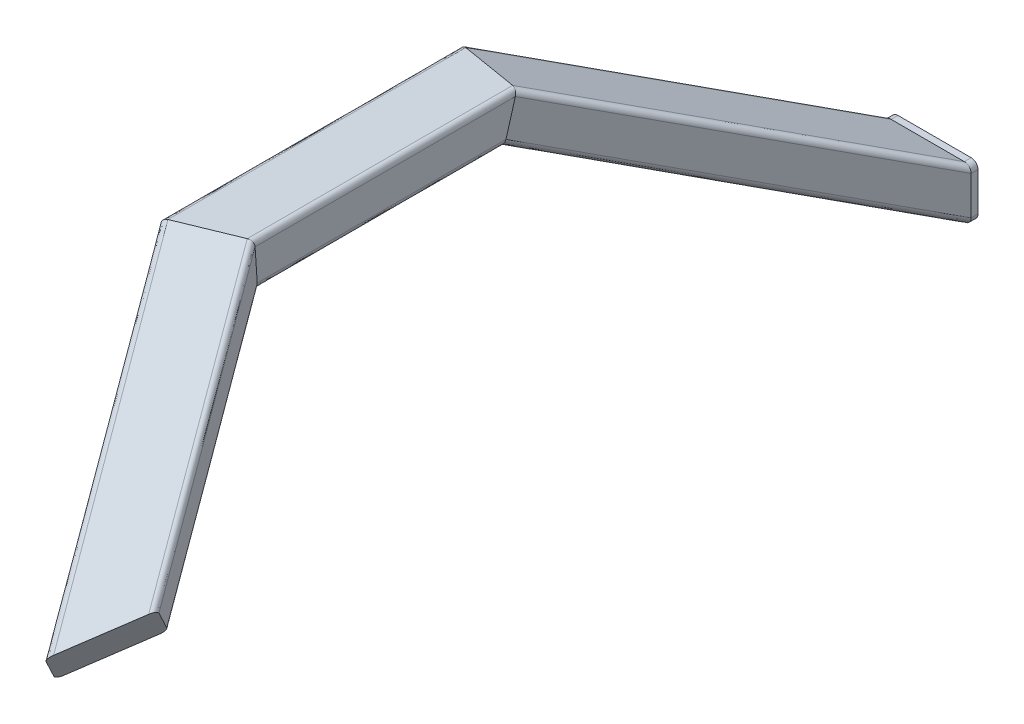
SolidWorks part; units mm, degrees
ref_plane "Alzado" through (0, 0, 0) normal (0, 0, 1) x (1, 0, 0)
ref_plane "Planta" through (0, 0, 0) normal (0, 1, 0) x (1, 0, 0)
ref_plane "Vista lateral" through (0, 0, 0) normal (1, 0, 0) x (0, 0, -1)
sketch "Croquis1" plane through (0, 0, 0) normal (0, 0, 1) x (1, 0, 0)
  line L1 (10, 0) -> (117, 0)
  line L2 (0, -10) -> (0, -66.2)
  line L3 (10, -76.2) -> (117, -76.2)
  line L4 (127, -10) -> (127, -66.2)
  arc A0 (0, -66.2) -> (10, -76.2) centre (10, -66.2) ccw
  arc A1 (117, -76.2) -> (127, -66.2) centre (117, -66.2) ccw
  arc A2 (117, 0) -> (127, -10) centre (117, -10) cw
  arc A3 (10, 0) -> (0, -10) centre (10, -10) ccw
  point P7 (0, -76.2)
  point P12 (127, 0)
  point P15 (0, 0)
  dimension "D3" = 10
  dimension "D1" = 127
  dimension "D2" = 76.2
extrude "Saliente-Extruir1" add sketch "Croquis1" along normal blind 10
sketch3d "Croquis3D1"
  line L0 (63.5, 0, 10) -> (63.5, -76.2, 10) construction
  line L1 (117, 0, 10) -> (10, 0, 10) construction
  line L2 (10, -76.2, 10) -> (117, -76.2, 10) construction
  line L3 (63.5, -38.1, 10) -> (63.5, -38.1, 410) construction
  line L4 (63.5, -38.1, 410) -> (63.5, -38.1, 1210) construction
  line L5 (-186.5, 131.9, 410) -> (-186.5, 131.9, 810)
  line L6 (63.5, -38.1, 410) -> (-186.5, -38.1, 410) construction
  line L7 (-186.5, -38.1, 410) -> (-186.5, 131.9, 410) construction
  line L8 (-186.5, 131.9, 810) -> (63.5, -38.1, 1210)
  line L9 (-186.5, 131.9, 410) -> (63.5, -38.1, 10)
  dimension "D1" = 400
  dimension "D2" = 250
  dimension "D3" = 170
  dimension "D4" = 800
  dimension "D5" = 400
sketch "Croquis2" plane through (0, 0, 10) normal (0, 0, 1) x (1, 0, 0)
  line L1 (10, -76.2) -> (117, -76.2)
  line L2 (0, -66.2) -> (0, -10)
  line L3 (10, 0) -> (117, 0)
  line L4 (127, -66.2) -> (127, -10)
  line L5 (0, -76.2) -> (127, 0) construction
  line L6 (0, 0) -> (127, -76.2) construction
  arc A0 (10, -76.2) -> (0, -66.2) centre (10, -66.2) cw
  arc A1 (117, -76.2) -> (127, -66.2) centre (117, -66.2) ccw
  arc A2 (117, 0) -> (127, -10) centre (117, -10) cw
  arc A3 (0, -10) -> (10, 0) centre (10, -10) cw
  point P0 (63.5, -38.1)
  dimension "D1" = 10
sweep "Barrer1" add profiles "Croquis2" path "Croquis3D1"
